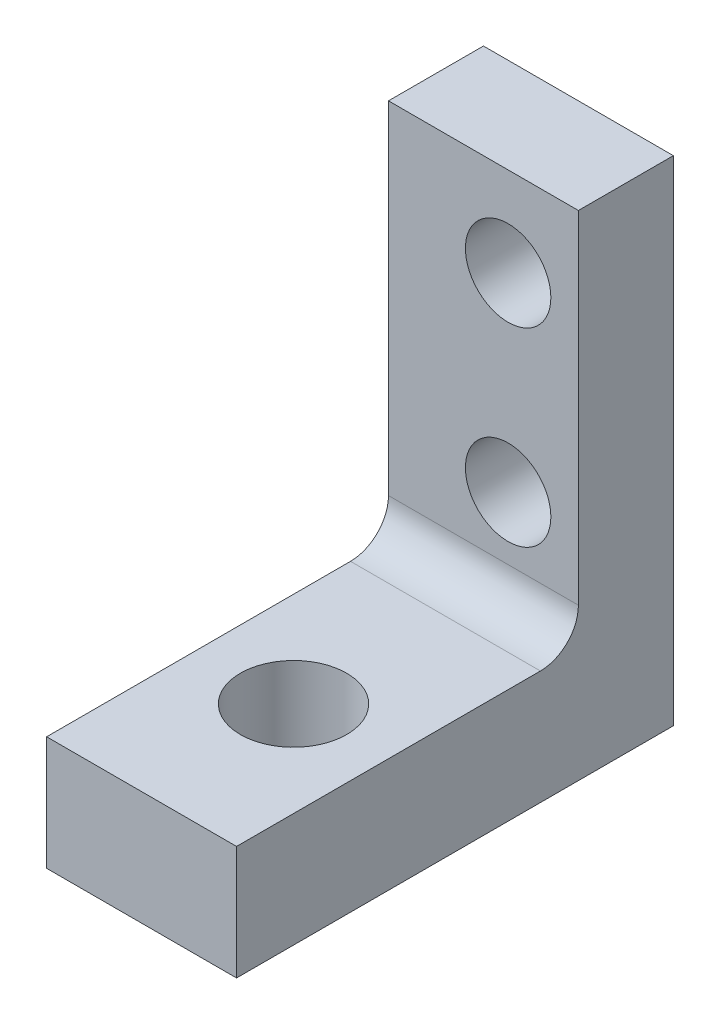
SolidWorks part; units mm, degrees
ref_plane "Front Plane" through (0, 0, 0) normal (0, 0, 1) x (1, 0, 0)
ref_plane "Top Plane" through (0, 0, 0) normal (0, 1, 0) x (1, 0, 0)
ref_plane "Right Plane" through (0, 0, 0) normal (1, 0, 0) x (0, 0, -1)
sketch "Sketch1" plane through (0, 0, 0) normal (0, 1, 0) x (1, 0, 0)
  line L0 (-5, 15) -> (-5, -8)
  line L5 (-5, -8) -> (5, -8)
  line L6 (5, -8) -> (5, 15)
  line L7 (5, 15) -> (-5, 15)
  circle A0 centre (0, 0) radius 2.8
  point P0 (0, 0)
  dimension "D3" = 5.6
  dimension "D1" = 10
  dimension "D2" = 5
  dimension "D4" = 0
  dimension "D5" = 8
  dimension "D6" = 15
extrude "Boss-Extrude1" add sketch "Sketch1" along normal blind 6 contours L0 L5 L6 L7 | A0
sketch "Sketch2" plane through (0, 6, 0) normal (0, 1, 0) x (1, 0, 0)
  line L0 (-5, 15) -> (5, 15)
  line L1 (5, 15) -> (-5, 15) construction
  line L2 (5, 15) -> (5, 10)
  line L3 (5, -8) -> (5, 15) construction
  line L4 (5, 10) -> (-5, 10)
  line L5 (-5, 15) -> (-5, -8) construction
  line L6 (-5, 10) -> (-5, 15)
  dimension "D1" = 5
extrude "Boss-Extrude2" add sketch "Sketch2" along normal blind 20
sketch "Sketch4" plane through (0, 0, -10) normal (0, 0, 1) x (1, 0, 0)
  line L0 (-5, 6) -> (5, 6) construction
  line L2 (5, 26) -> (5, 6) construction
  circle A0 centre (1.3, 11.3) radius 2.25
  circle A1 centre (1.3, 21.3) radius 2.25
  dimension "D2" = 4.5
  dimension "D1" = 5.3
  dimension "D3" = 3.7
  dimension "D4" = 2
extrude "Cut-Extrude1" cut sketch "Sketch4" against normal blind 10
fillet "Fillet1" radius 2 1 edges at (0, 6, -10)
